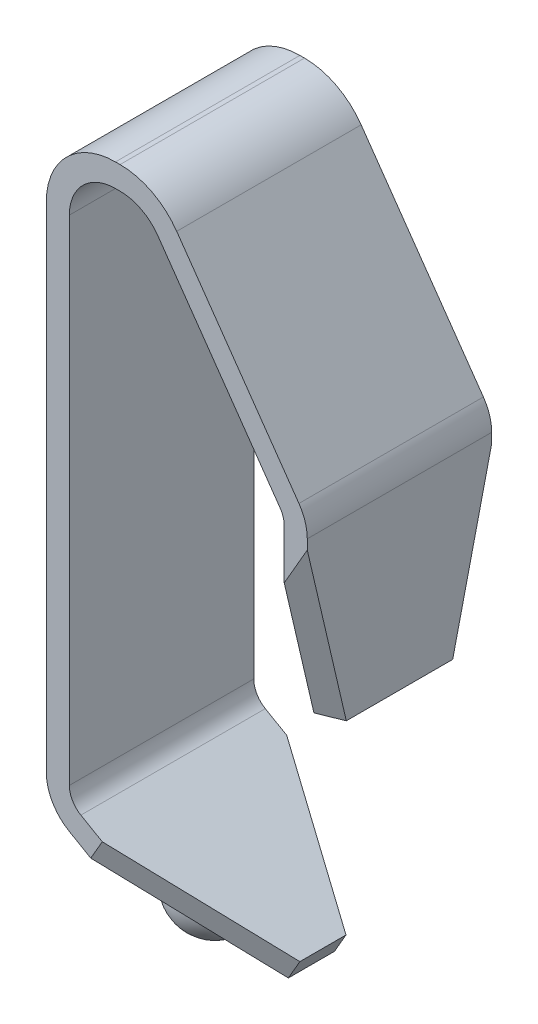
SolidWorks part; units mm, degrees
ref_plane "Front Plane" through (0, 0, 0) normal (0, 0, 1) x (1, 0, 0)
ref_plane "Top Plane" through (0, 0, 0) normal (0, 1, 0) x (1, 0, 0)
ref_plane "Right Plane" through (0, 0, 0) normal (1, 0, 0) x (0, 0, -1)
sketch "Sketch1" plane through (0, 0, 0) normal (0, 0, 1) x (1, 0, 0)
  line L0 (0, 0.2887) -> (0, 11)
  line L1 (1, 12) -> (1.1, 12)
  line L2 (1.9192, 11.5736) -> (4.5701, 7.7876)
  line L3 (0.25, -0.1443) -> (3.5, -2.0207)
  line L4 (4.6605, 7.5008) -> (4.6605, 3.6585)
  arc A0 (0, 0.2887) -> (0.25, -0.1443) centre (0.5, 0.2887) ccw
  arc A1 (1.1, 12) -> (1.9192, 11.5736) centre (1.1, 11) cw
  arc A2 (0, 11) -> (1, 12) centre (1, 11) cw
  arc A3 (4.5701, 7.7876) -> (4.6605, 7.5008) centre (4.1605, 7.5008) cw
  point P8 (0, 0)
  point P11 (1.6206, 12)
  point P14 (0, 12)
  point P18 (4.6605, 7.6585)
  dimension "D7" = 0.5
  dimension "D8" = 1
  dimension "D10" = 0.5
  dimension "D1" = 12
  dimension "D2" = 0.1
  dimension "D3" = 5.3
  dimension "D4" = 125
  dimension "D5" = 120
  dimension "D6" = 3.5
  dimension "D9" = 4
extrude "Extrude-Thin1" add sketch "Sketch1" along normal mid plane 4 thin thin type one direction wall 0.5
sketch "Sketch3" plane through (0, 0, 0) normal (0.5, 0.866, 0) x (0.866, -0.5, 0)
  line L0 (0.8247, 2) -> (4.0415, 0.5)
  line L1 (0.2887, 2) -> (4.0415, 2) construction
  line L2 (4.0415, -2) -> (4.0415, 2) construction
  line L3 (4.0415, -0.5) -> (0.8247, -2)
  line L4 (0.2887, -2) -> (4.0415, -2) construction
  line L5 (0.8247, 2) -> (0.8247, 2.9615)
  line L6 (0.8247, 2.9615) -> (5.0598, 2.9615)
  line L7 (5.0598, 2.9615) -> (5.0598, -2.582)
  line L8 (5.0598, -2.582) -> (0.8247, -2.582)
  line L9 (0.8247, -2.582) -> (0.8247, -2)
  dimension "D1" = 25
  dimension "D2" = 1.5
  dimension "D3" = 25
  dimension "D4" = 1.5
extrude "Cut-Extrude1" cut sketch "Sketch3" against normal through all and the other way through all
sketch "Sketch5" plane through (-0.25, -0.433, 0) normal (-0.5, -0.866, 0) x (0.866, -0.5, 0)
  line L0 (4.0415, 0.5) -> (4.0415, -0.5) construction
  point P0 (2, 0)
  dimension "D2" = 2
sketch "Sketch6" plane through (0, 0, 0) normal (0, 0, 1) x (1, 0, 0)
  line L0 (1.4821, -1.433) -> (0.7321, -2.7321) construction
  line L1 (0.4642, -0.8454) -> (3.25, -2.4537) construction
  line L2 (1.4821, -1.433) -> (2.0017, -1.733)
  line L3 (0.7321, -2.7321) -> (0.0941, -2.3637) construction
  line L4 (1.4821, -1.433) -> (0.7321, -2.7321)
  arc A0 (2.0017, -1.733) -> (0.7321, -2.7321) centre (1.1671, -1.9786) cw
  dimension "D1" = 1.5
  dimension "D2" = 0.6
revolve "Revolve1" add sketch "Sketch6" angle 360 about L4
equation "\"D3@Sketch3\"=\"D1@Sketch3\""
equation "\"D4@Sketch3\"=\"D2@Sketch3\""
